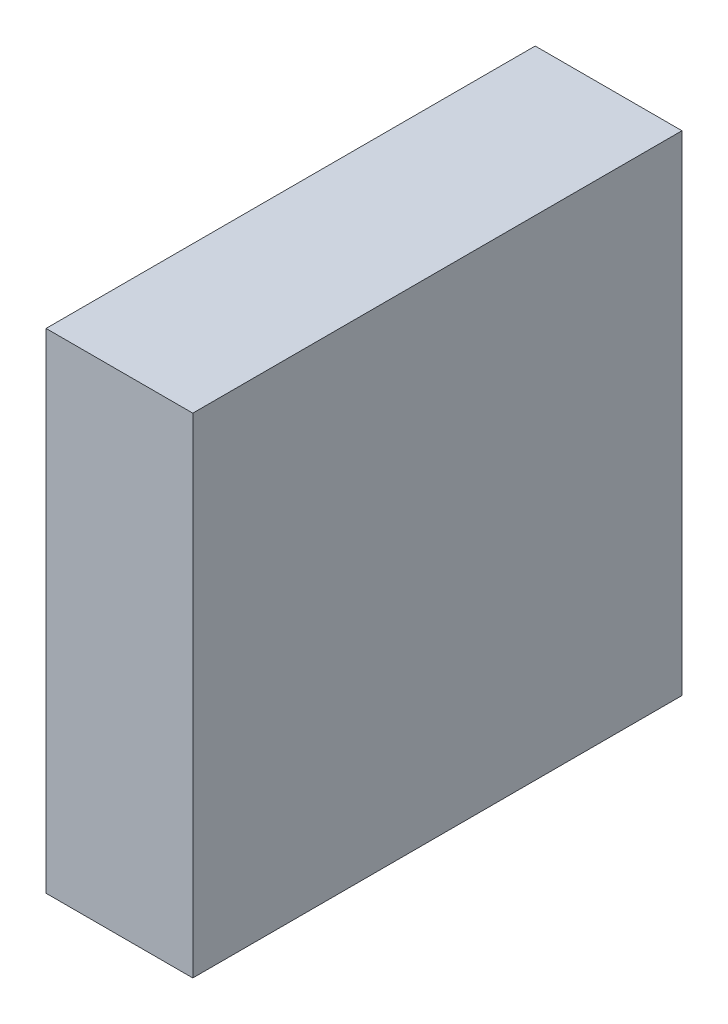
SolidWorks part; units mm, degrees
ref_plane "Plano frontal" through (0, 0, 0) normal (0, 0, 1) x (1, 0, 0)
ref_plane "Plano superior" through (0, 0, 0) normal (0, 1, 0) x (1, 0, 0)
ref_plane "Plano direito" through (0, 0, 0) normal (1, 0, 0) x (0, 0, -1)
sketch "Esboço1" plane through (0, 0, 0) normal (1, 0, 0) x (0, 0, -1)
  line L1 (0, 0) -> (-500, 0)
  line L2 (0, 0) -> (0, 500)
  line L3 (0, 500) -> (-500, 500)
  line L4 (-500, 0) -> (-500, 500)
  dimension "D1" = 500
  dimension "D2" = 500
extrude "Ressalto-extrusão1" add sketch "Esboço1" along normal blind 150
